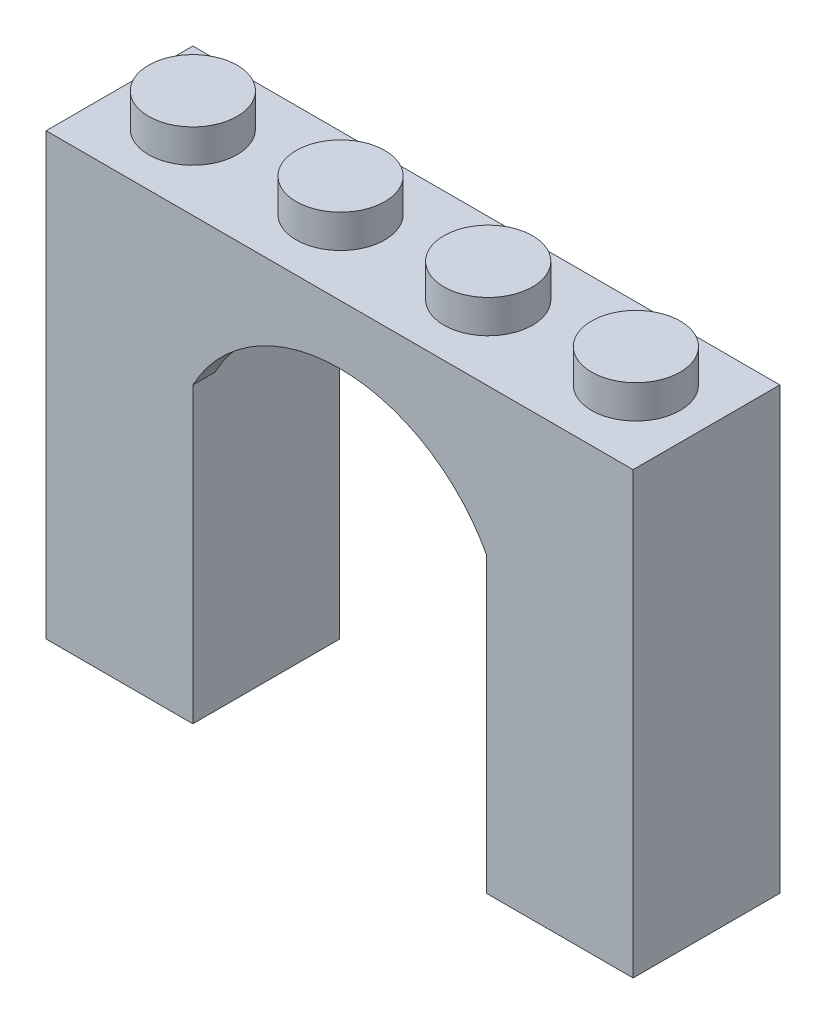
SolidWorks part; units mm, degrees
ref_plane "Front Plane" through (0, 0, 0) normal (0, 0, 1) x (1, 0, 0)
ref_plane "Top Plane" through (0, 0, 0) normal (0, 1, 0) x (1, 0, 0)
ref_plane "Right Plane" through (0, 0, 0) normal (1, 0, 0) x (0, 0, -1)
sketch "Sketch1" plane through (0, 0, 0) normal (0, 0, 1) x (1, 0, 0)
  line L0 (-7.95, 0) -> (-15.9, 0)
  line L1 (-15.9, 0) -> (-15.9, 23.85)
  line L2 (-7.95, 0) -> (-7.95, 15.9)
  line L3 (7.95, 0) -> (7.95, 15.9)
  line L4 (7.95, 0) -> (15.9, 0)
  line L5 (15.9, 0) -> (15.9, 23.85)
  line L6 (-15.9, 23.85) -> (15.9, 23.85)
  line L7 (0, 0) -> (0, 47.7) construction
  arc A0 (-7.95, 15.9) -> (7.95, 15.9) centre (0, 11.6221) cw
  point P11 (0, 23.85)
  point P13 (0, 20.65)
  dimension "D1" = 15.9
  dimension "D2" = 7.95
  dimension "D3" = 23.85
  dimension "D4" = 3.2
  dimension "D5" = 15.9
extrude "Boss-Extrude1" add sketch "Sketch1" against normal blind 7.95
sketch "Sketch2" plane through (0, 23.85, 0) normal (0, 1, 0) x (1, 0, 0)
  line L0 (15.9, 7.95) -> (-15.9, 7.95) construction
  line L2 (-15.9, 7.95) -> (-15.9, 0) construction
  circle A0 centre (-12, 4.05) radius 2.4
  dimension "D1" = 4.8
  dimension "D2" = 3.9
  dimension "D3" = 3.9
extrude "Boss-Extrude2" add sketch "Sketch2" along normal blind 1.8
pattern_linear "LPattern1" count 4 spacing 8 along (1, 0, 0) of "Boss-Extrude2"
shell "Shell3" thickness 1.2
sketch "Sketch3" plane through (0, 23.85, 0) normal (0, 1, 0) x (1, 0, 0)
  line L0 (15.9, 7.95) -> (-15.9, 7.95) construction
  line L1 (-7.95, 1.2) -> (7.95, 1.2)
  line L2 (-7.95, 1.2) -> (-7.95, 6.75)
  line L3 (-7.95, 6.75) -> (7.95, 6.75)
  line L4 (7.95, 1.2) -> (7.95, 6.75)
  line L5 (-7.95, 1.2) -> (7.95, 6.75) construction
  line L6 (-7.95, 6.75) -> (7.95, 1.2) construction
  line L7 (15.9, 0) -> (-15.9, 0) construction
  point P0 (0, 3.975)
  point P9 (0, 0)
  dimension "D1" = 1.2
  dimension "D2" = 15.9
  dimension "D3" = 1.2
extrude "Cut-Extrude1" cut sketch "Sketch3" against normal through all from offset 1.2
